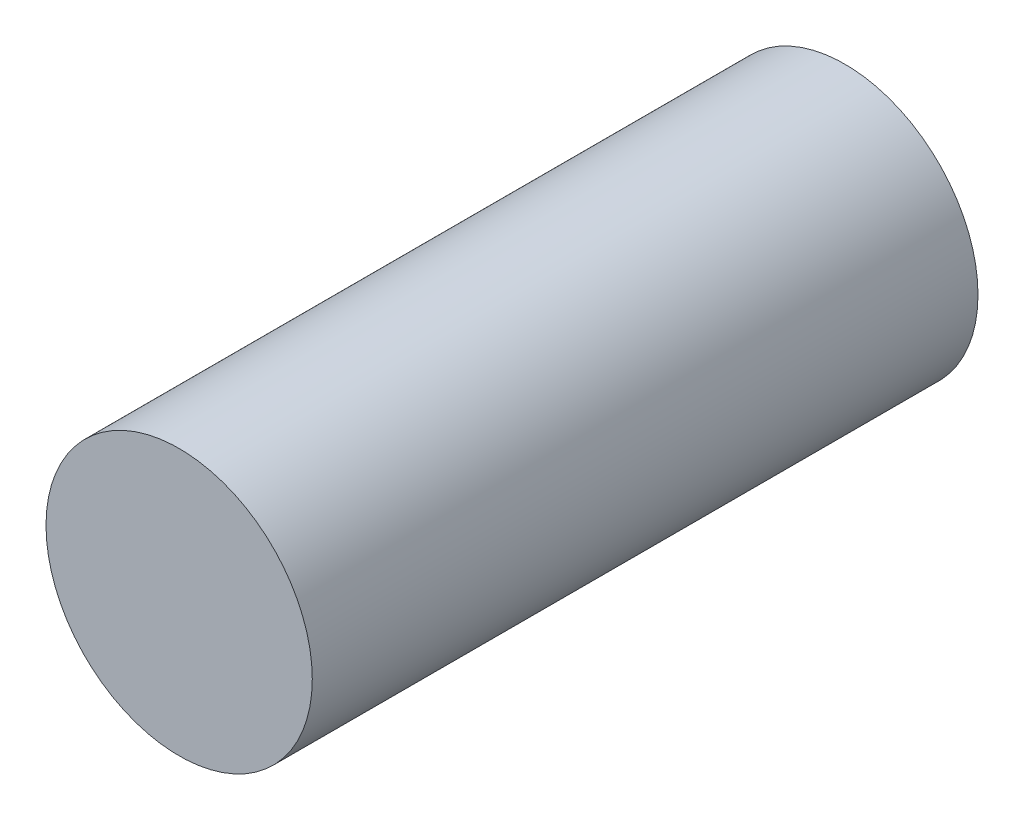
SolidWorks part; units mm, degrees
ref_plane "Front Plane" through (0, 0, 0) normal (0, 0, 1) x (1, 0, 0)
ref_plane "Top Plane" through (0, 0, 0) normal (0, 1, 0) x (1, 0, 0)
ref_plane "Right Plane" through (0, 0, 0) normal (1, 0, 0) x (0, 0, -1)
sketch "Sketch1" plane through (0, 0, 0) normal (0, 0, 1) x (1, 0, 0)
  circle A0 centre (0, 0) radius 1
  dimension "D1" = 2
extrude "Boss-Extrude1" add sketch "Sketch1" along normal blind 5
